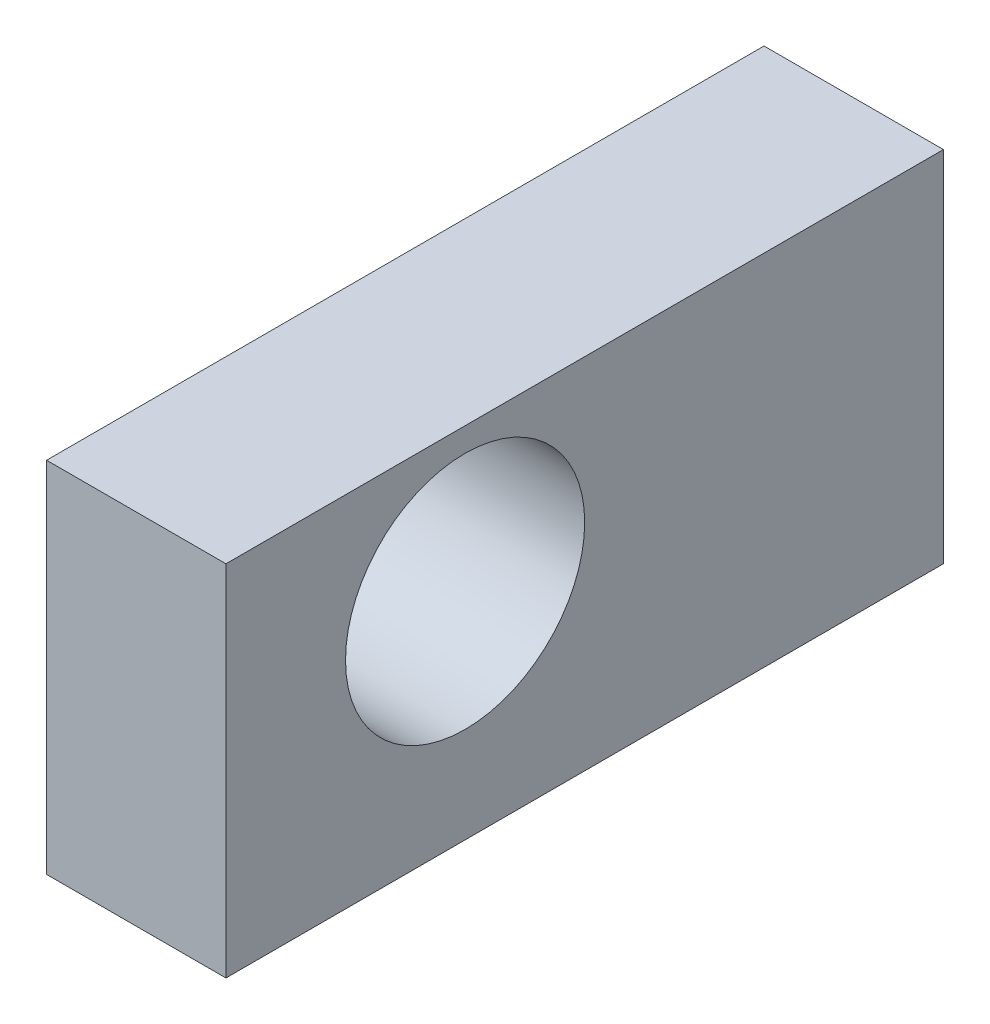
SolidWorks part; units mm, degrees
material "1060 Alloy"
ref_plane "Front Plane" through (0, 0, 0) normal (0, 0, 1) x (1, 0, 0)
ref_plane "Top Plane" through (0, 0, 0) normal (0, 1, 0) x (1, 0, 0)
ref_plane "Right Plane" through (0, 0, 0) normal (1, 0, 0) x (0, 0, -1)
sketch "Sketch1" plane through (0, 0, 0) normal (1, 0, 0) x (0, 0, -1)
  line L1 (-19.05, -9.525) -> (19.05, -9.525)
  line L2 (-19.05, -9.525) -> (-19.05, 9.525)
  line L3 (-19.05, 9.525) -> (19.05, 9.525)
  line L4 (19.05, -9.525) -> (19.05, 9.525)
  line L5 (-19.05, -9.525) -> (19.05, 9.525) construction
  line L6 (-19.05, 9.525) -> (19.05, -9.525) construction
  point P0 (0, 0)
  dimension "D1" = 38.1
  dimension "D2" = 19.05
extrude "Boss-Extrude1" add sketch "Sketch1" along normal blind 9.525
hole_wizard "1/2 (0.5) Diameter Hole1" positions "Sketch9" profile "Sketch8" hole size "1/2" standard "ANSI Inch"
sketch "Sketch9" plane through (9.525, 0, 0) normal (1, 0, 0) x (0, 0, -1)
  line L0 (-19.05, -9.525) -> (19.05, -9.525) construction
  line L1 (19.05, -9.525) -> (19.05, 9.525) construction
  point P0 (-6.35, 1.905)
  dimension "D2" = 25.4
  dimension "D1" = 11.43
sketch "Sketch8" plane through (9.525, 1.905, 6.35) normal (0, 1, 0) x (0, 0, -1)
  line L0 (0, 0) -> (0, 73.9195)
  line L1 (0, 73.9195) -> (6.35, 70.104)
  line L2 (6.35, 70.104) -> (6.35, 0)
  line L5 (6.35, 0) -> (0, 0)
  line L10 (0, 73.9195) -> (-6.35, 70.104) construction
  line L11 (0, -6.35) -> (0, 107.95) construction
  dimension "Hole Dia." = 12.7
  dimension "Hole Depth" = 70.104
  dimension "Drill Angle" = 118
hole_wizard "#10-32 Tapped Hole1" positions "Sketch11" profile "Sketch10" tap size "#10-32" standard "ANSI Inch"
sketch "Sketch11" plane through (-1.1365, 0.5118, -19.05) normal (0, 0, -1) x (-1, 0, 0)
  line L0 (-10.6615, 9.0132) -> (-1.1365, 9.0132) construction
  line L2 (-10.6615, -10.0368) -> (-1.1365, -10.0368) construction
  line L3 (-10.6615, 9.0132) -> (-1.1365, 9.0132) construction
  point P0 (-5.899, -3.6868)
  point P2 (-5.899, 5.2032)
  point P6 (-5.899, 9.0132)
  dimension "D1" = 0
  dimension "D2" = 0
  dimension "D3" = 3.81
  dimension "D4" = 6.35
sketch "Sketch10" plane through (4.7625, -3.175, -19.05) normal (1, 0, 0) x (0, 1, 0)
  line L0 (0, 0) -> (0, 13.1513)
  line L1 (0, 13.1513) -> (2.0193, 11.938)
  line L2 (2.0193, 11.938) -> (2.0193, 0)
  line L5 (2.0193, 0) -> (0, 0)
  line L10 (0, 13.1513) -> (-2.0193, 11.938) construction
  line L11 (0, -6.35) -> (0, 107.95) construction
  dimension "Tap Drill Dia." = 4.0386
  dimension "Tap Drill Depth" = 11.938
  dimension "Drill Angle" = 118
cosmetic thread "Hole Thread1"
cosmetic thread "Hole Thread2"
